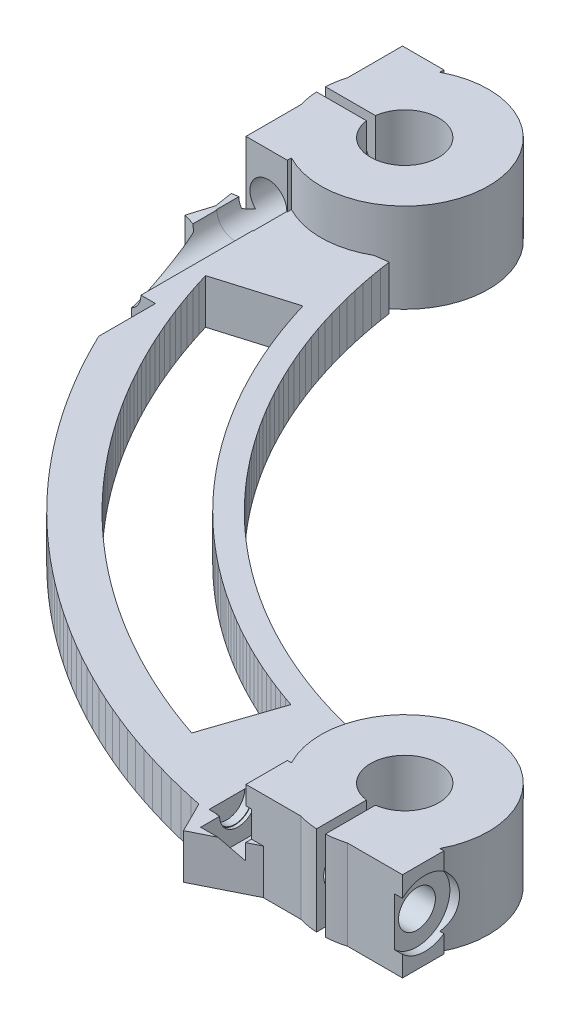
SolidWorks part; units mm, degrees
other "Suspension Travel Stop Plate"
ref_plane "Front Plane" through (0, 0, 0) normal (0, 0, 1) x (1, 0, 0)
ref_plane "Top Plane" through (0, 0, 0) normal (0, 1, 0) x (1, 0, 0)
ref_plane "Right Plane" through (0, 0, 0) normal (1, 0, 0) x (0, 0, -1)
sketch3d "Main Profile Sketch datum points"
  point P0 (0, -120, 0)
  point P1 (10, -120, 0)
  point P2 (0, -120, 10)
ref_plane "Main Profile Sketch plane" through (0, -120, 0) normal (0, -1, 0) x (-1, 0, 0)
sketch "Main Profile Sketch" plane through (0, -120, 0) normal (0, -1, 0) x (-1, 0, 0)
  line L0 (49.2917, -53.5) -> (49.2917, -57.2)
  line L1 (49.2917, -57.2) -> (54.1917, -57.2)
  line L2 (55.8917, -53.0237) -> (55.8917, -57.4893)
  line L3 (56.6917, -53.0237) -> (56.6917, -57.4893)
  line L4 (58.3917, -57.2) -> (61.7474, -57.2)
  line L5 (61.7474, -57.2) -> (66.5028, -59.5777)
  line L6 (66.5028, -59.5777) -> (67.8774, -56.8285)
  line L7 (68.7463, -56.647) -> (67.8774, -56.8285)
  line L8 (69.9299, -56.3737) -> (68.7463, -56.647)
  line L9 (71.1075, -56.0758) -> (69.9299, -56.3737)
  line L10 (72.2786, -55.7532) -> (71.1075, -56.0758)
  line L11 (73.4427, -55.4061) -> (72.2786, -55.7532)
  line L12 (74.5993, -55.0348) -> (73.4427, -55.4061)
  line L13 (75.7478, -54.6393) -> (74.5993, -55.0348)
  line L14 (76.8879, -54.2199) -> (75.7478, -54.6393)
  line L15 (78.0188, -53.7767) -> (76.8879, -54.2199)
  line L16 (79.1403, -53.3098) -> (78.0188, -53.7767)
  line L17 (80.2517, -52.8197) -> (79.1403, -53.3098)
  line L18 (81.3526, -52.3063) -> (80.2517, -52.8197)
  line L19 (82.4425, -51.77) -> (81.3526, -52.3063)
  line L20 (83.521, -51.211) -> (82.4425, -51.77)
  line L21 (84.5875, -50.6295) -> (83.521, -51.211)
  line L22 (85.6416, -50.0258) -> (84.5875, -50.6295)
  line L23 (86.6828, -49.4002) -> (85.6416, -50.0258)
  line L24 (87.7107, -48.7529) -> (86.6828, -49.4002)
  line L25 (88.7248, -48.0842) -> (87.7107, -48.7529)
  line L26 (89.7247, -47.3944) -> (88.7248, -48.0842)
  line L27 (90.7099, -46.6838) -> (89.7247, -47.3944)
  line L28 (91.6801, -45.9528) -> (90.7099, -46.6838)
  line L29 (92.6347, -45.2016) -> (91.6801, -45.9528)
  line L30 (93.5733, -44.4306) -> (92.6347, -45.2016)
  line L31 (94.4956, -43.6401) -> (93.5733, -44.4306)
  line L32 (95.4012, -42.8304) -> (94.4956, -43.6401)
  line L33 (96.2896, -42.002) -> (95.4012, -42.8304)
  line L34 (97.1604, -41.1551) -> (96.2896, -42.002)
  line L35 (98.0134, -40.2902) -> (97.1604, -41.1551)
  line L36 (98.848, -39.4076) -> (98.0134, -40.2902)
  line L37 (99.6639, -38.5077) -> (98.848, -39.4076)
  line L38 (100.4609, -37.591) -> (99.6639, -38.5077)
  line L39 (101.2384, -36.6577) -> (100.4609, -37.591)
  line L40 (101.9963, -35.7084) -> (101.2384, -36.6577)
  line L41 (102.7341, -34.7434) -> (101.9963, -35.7084)
  line L42 (103.4515, -33.7631) -> (102.7341, -34.7434)
  line L43 (104.1482, -32.7681) -> (103.4515, -33.7631)
  line L44 (104.824, -31.7587) -> (104.1482, -32.7681)
  line L45 (105.4784, -30.7353) -> (104.824, -31.7587)
  line L46 (106.1113, -29.6985) -> (105.4784, -30.7353)
  line L47 (106.7224, -28.6486) -> (106.1113, -29.6985)
  line L48 (107.3113, -27.5862) -> (106.7224, -28.6486)
  line L49 (107.8778, -26.5117) -> (107.3113, -27.5862)
  line L50 (108.4217, -25.4255) -> (107.8778, -26.5117)
  line L51 (108.9427, -24.3282) -> (108.4217, -25.4255)
  line L52 (109.4407, -23.2202) -> (108.9427, -24.3282)
  line L53 (109.9153, -22.1021) -> (109.4407, -23.2202)
  line L54 (110.3664, -20.9742) -> (109.9153, -22.1021)
  line L55 (110.7938, -19.8372) -> (110.3664, -20.9742)
  line L56 (111.1973, -18.6914) -> (110.7938, -19.8372)
  line L57 (111.5767, -17.5375) -> (111.1973, -18.6914)
  line L58 (111.9319, -16.3758) -> (111.5767, -17.5375)
  line L59 (112.2626, -15.207) -> (111.9319, -16.3758)
  line L60 (112.5688, -14.0315) -> (112.2626, -15.207)
  line L61 (112.8503, -12.8498) -> (112.5688, -14.0315)
  line L62 (112.9979, -12.1673) -> (112.8503, -12.8498)
  line L63 (112.9979, -12.1673) -> (114.1148, -11.8237)
  line L64 (114.1148, -11.8237) -> (113.468, -9.7218)
  line L65 (113.5456, -9.2731) -> (113.468, -9.7218)
  line L66 (113.7272, -8.072) -> (113.5456, -9.2731)
  line L67 (112.9258, -7.9594) -> (113.7272, -8.072)
  line L68 (112.9258, -7.9594) -> (112.6306, -7)
  line L69 (112.6306, -7) -> (113.4917, -7)
  line L70 (113.4917, -2.1) -> (113.4917, -7)
  line L71 (109.2649, -0.4) -> (113.781, -0.4)
  line L72 (103.4243, -0.8823) -> (103.3765, -0.897)
  line L73 (109.2068, 0.897) -> (109.159, 0.8823)
  line L74 (109.2649, 0.4) -> (113.781, 0.4)
  line L75 (113.4917, 7) -> (113.4917, 2.1)
  line L76 (109.7917, 7) -> (113.4917, 7)
  line L77 (109.7917, 7) -> (109.7917, 6.6332)
  line L78 (101.3488, -6.3324) -> (102.5527, -6.5016)
  line L79 (101.2064, -7.2746) -> (101.3488, -6.3324)
  line L80 (101.0442, -8.2136) -> (101.2064, -7.2746)
  line L81 (100.8623, -9.149) -> (101.0442, -8.2136)
  line L82 (100.6609, -10.0805) -> (100.8623, -9.149)
  line L83 (100.4401, -11.0074) -> (100.6609, -10.0805)
  line L84 (100.1999, -11.9296) -> (100.4401, -11.0074)
  line L85 (99.9404, -12.8465) -> (100.1999, -11.9296)
  line L86 (99.6618, -13.7578) -> (99.9404, -12.8465)
  line L87 (99.3642, -14.6631) -> (99.6618, -13.7578)
  line L88 (99.0477, -15.5619) -> (99.3642, -14.6631)
  line L89 (98.7124, -16.4539) -> (99.0477, -15.5619)
  line L90 (98.3585, -17.3387) -> (98.7124, -16.4539)
  line L91 (97.9862, -18.2159) -> (98.3585, -17.3387)
  line L92 (97.5955, -19.0851) -> (97.9862, -18.2159)
  line L93 (97.1868, -19.9459) -> (97.5955, -19.0851)
  line L94 (96.7601, -20.798) -> (97.1868, -19.9459)
  line L95 (96.3157, -21.6409) -> (96.7601, -20.798)
  line L96 (95.8537, -22.4744) -> (96.3157, -21.6409)
  line L97 (95.3743, -23.298) -> (95.8537, -22.4744)
  line L98 (94.8778, -24.1113) -> (95.3743, -23.298)
  line L99 (94.3644, -24.9141) -> (94.8778, -24.1113)
  line L100 (93.8343, -25.706) -> (94.3644, -24.9141)
  line L101 (93.2877, -26.4866) -> (93.8343, -25.706)
  line L102 (92.7249, -27.2556) -> (93.2877, -26.4866)
  line L103 (92.1461, -28.0126) -> (92.7249, -27.2556)
  line L104 (91.5516, -28.7573) -> (92.1461, -28.0126)
  line L105 (90.9416, -29.4895) -> (91.5516, -28.7573)
  line L106 (90.3165, -30.2086) -> (90.9416, -29.4895)
  line L107 (89.6764, -30.9146) -> (90.3165, -30.2086)
  line L108 (89.0216, -31.607) -> (89.6764, -30.9146)
  line L109 (88.3525, -32.2855) -> (89.0216, -31.607)
  line L110 (87.6693, -32.9498) -> (88.3525, -32.2855)
  line L111 (86.9724, -33.5997) -> (87.6693, -32.9498)
  line L112 (86.262, -34.2349) -> (86.9724, -33.5997)
  line L113 (85.5385, -34.855) -> (86.262, -34.2349)
  line L114 (84.8021, -35.4599) -> (85.5385, -34.855)
  line L115 (84.0533, -36.0492) -> (84.8021, -35.4599)
  line L116 (83.2922, -36.6227) -> (84.0533, -36.0492)
  line L117 (82.5193, -37.1801) -> (83.2922, -36.6227)
  line L118 (81.7349, -37.7212) -> (82.5193, -37.1801)
  line L119 (80.9394, -38.2458) -> (81.7349, -37.7212)
  line L120 (80.133, -38.7536) -> (80.9394, -38.2458)
  line L121 (79.3162, -39.2444) -> (80.133, -38.7536)
  line L122 (78.4893, -39.718) -> (79.3162, -39.2444)
  line L123 (77.6526, -40.1741) -> (78.4893, -39.718)
  line L124 (76.8066, -40.6127) -> (77.6526, -40.1741)
  line L125 (75.9516, -41.0334) -> (76.8066, -40.6127)
  line L126 (75.0879, -41.4361) -> (75.9516, -41.0334)
  line L127 (74.216, -41.8207) -> (75.0879, -41.4361)
  line L128 (73.3363, -42.1869) -> (74.216, -41.8207)
  line L129 (72.449, -42.5346) -> (73.3363, -42.1869)
  line L130 (71.5547, -42.8636) -> (72.449, -42.5346)
  line L131 (70.6537, -43.1739) -> (71.5547, -42.8636)
  line L132 (69.7464, -43.4652) -> (70.6537, -43.1739)
  line L133 (68.8332, -43.7374) -> (69.7464, -43.4652)
  line L134 (67.9144, -43.9905) -> (68.8332, -43.7374)
  line L135 (66.9906, -44.2242) -> (67.9144, -43.9905)
  line L136 (66.0621, -44.4386) -> (66.9906, -44.2242)
  line L137 (65.1293, -44.6335) -> (66.0621, -44.4386)
  line L138 (64.1926, -44.8088) -> (65.1293, -44.6335)
  line L139 (65.0956, -49.9299) -> (64.1926, -44.8088)
  line L140 (65.0956, -49.9299) -> (63.755, -49.2595)
  line L141 (49.2917, -53.5) -> (49.6584, -53.5)
  line L142 (100.8479, -16.4618) -> (101.1044, -15.7502)
  line L143 (101.1044, -15.7502) -> (101.3495, -15.0346)
  line L144 (101.3495, -15.0346) -> (101.5832, -14.3152)
  line L145 (101.5832, -14.3152) -> (101.8054, -13.5922)
  line L146 (101.8054, -13.5922) -> (108.5127, -15.5953)
  line L147 (108.5127, -15.5953) -> (108.2577, -16.4249)
  line L148 (108.2577, -16.4249) -> (107.9896, -17.2503)
  line L149 (107.9896, -17.2503) -> (107.7084, -18.0713)
  line L150 (107.7084, -18.0713) -> (107.4141, -18.8878)
  line L151 (107.4141, -18.8878) -> (107.1068, -19.6995)
  line L152 (107.1068, -19.6995) -> (106.7867, -20.5061)
  line L153 (106.7867, -20.5061) -> (106.4537, -21.3076)
  line L154 (106.4537, -21.3076) -> (106.1081, -22.1037)
  line L155 (106.1081, -22.1037) -> (105.7498, -22.8942)
  line L156 (105.7498, -22.8942) -> (105.379, -23.6788)
  line L157 (105.379, -23.6788) -> (104.9957, -24.4575)
  line L158 (104.9957, -24.4575) -> (104.6, -25.2299)
  line L159 (104.6, -25.2299) -> (104.1922, -25.996)
  line L160 (104.1922, -25.996) -> (103.7721, -26.7555)
  line L161 (103.7721, -26.7555) -> (103.3401, -27.5081)
  line L162 (103.3401, -27.5081) -> (102.8961, -28.2538)
  line L163 (102.8961, -28.2538) -> (102.4402, -28.9924)
  line L164 (102.4402, -28.9924) -> (101.9727, -29.7236)
  line L165 (101.9727, -29.7236) -> (101.4936, -30.4472)
  line L166 (101.4936, -30.4472) -> (101.003, -31.1631)
  line L167 (101.003, -31.1631) -> (100.5011, -31.8712)
  line L168 (100.5011, -31.8712) -> (99.988, -32.5711)
  line L169 (99.988, -32.5711) -> (99.4638, -33.2628)
  line L170 (99.4638, -33.2628) -> (98.9287, -33.9461)
  line L171 (98.9287, -33.9461) -> (98.3827, -34.6207)
  line L172 (98.3827, -34.6207) -> (97.8261, -35.2866)
  line L173 (97.8261, -35.2866) -> (97.2589, -35.9435)
  line L174 (97.2589, -35.9435) -> (96.6814, -36.5913)
  line L175 (96.6814, -36.5913) -> (96.0936, -37.2298)
  line L176 (96.0936, -37.2298) -> (95.4957, -37.8589)
  line L177 (95.4957, -37.8589) -> (94.8878, -38.4784)
  line L178 (94.8878, -38.4784) -> (94.2702, -39.0881)
  line L179 (94.2702, -39.0881) -> (93.643, -39.6879)
  line L180 (93.643, -39.6879) -> (93.0063, -40.2776)
  line L181 (93.0063, -40.2776) -> (92.3602, -40.8572)
  line L182 (92.3602, -40.8572) -> (91.705, -41.4263)
  line L183 (91.705, -41.4263) -> (91.0409, -41.985)
  line L184 (91.0409, -41.985) -> (90.3679, -42.533)
  line L185 (90.3679, -42.533) -> (89.6863, -43.0703)
  line L186 (89.6863, -43.0703) -> (88.9962, -43.5966)
  line L187 (88.9962, -43.5966) -> (88.2978, -44.1118)
  line L188 (88.2978, -44.1118) -> (87.5914, -44.6159)
  line L189 (87.5914, -44.6159) -> (86.8769, -45.1087)
  line L190 (86.8769, -45.1087) -> (86.1547, -45.59)
  line L191 (86.1547, -45.59) -> (85.425, -46.0597)
  line L192 (85.425, -46.0597) -> (84.6879, -46.5178)
  line L193 (84.6879, -46.5178) -> (83.9435, -46.9641)
  line L194 (83.9435, -46.9641) -> (83.1922, -47.3985)
  line L195 (83.1922, -47.3985) -> (82.434, -47.8208)
  line L196 (82.434, -47.8208) -> (81.6692, -48.231)
  line L197 (81.6692, -48.231) -> (80.8979, -48.629)
  line L198 (80.8979, -48.629) -> (80.1204, -49.0147)
  line L199 (80.1204, -49.0147) -> (79.3369, -49.3879)
  line L200 (79.3369, -49.3879) -> (78.5475, -49.7486)
  line L201 (78.5475, -49.7486) -> (77.7525, -50.0967)
  line L202 (77.7525, -50.0967) -> (76.9521, -50.4321)
  line L203 (76.9521, -50.4321) -> (76.1464, -50.7547)
  line L204 (76.1464, -50.7547) -> (75.3357, -51.0644)
  line L205 (75.3357, -51.0644) -> (74.5201, -51.3612)
  line L206 (74.5201, -51.3612) -> (73.6999, -51.645)
  line L207 (73.6999, -51.645) -> (71.464, -45.0117)
  line L208 (71.464, -45.0117) -> (72.1788, -44.7644)
  line L209 (72.1788, -44.7644) -> (72.8896, -44.5057)
  line L210 (72.8896, -44.5057) -> (73.5962, -44.2357)
  line L211 (73.5962, -44.2357) -> (74.2984, -43.9546)
  line L212 (74.2984, -43.9546) -> (74.9961, -43.6623)
  line L213 (74.9961, -43.6623) -> (75.689, -43.3589)
  line L214 (75.689, -43.3589) -> (76.377, -43.0445)
  line L215 (76.377, -43.0445) -> (77.0599, -42.7192)
  line L216 (77.0599, -42.7192) -> (77.7375, -42.3831)
  line L217 (77.7375, -42.3831) -> (78.4097, -42.0362)
  line L218 (78.4097, -42.0362) -> (79.0762, -41.6787)
  line L219 (79.0762, -41.6787) -> (79.737, -41.3106)
  line L220 (79.737, -41.3106) -> (80.3919, -40.932)
  line L221 (80.3919, -40.932) -> (81.0406, -40.543)
  line L222 (81.0406, -40.543) -> (81.6831, -40.1438)
  line L223 (81.6831, -40.1438) -> (82.3191, -39.7344)
  line L224 (82.3191, -39.7344) -> (82.9485, -39.3149)
  line L225 (82.9485, -39.3149) -> (83.5712, -38.8854)
  line L226 (83.5712, -38.8854) -> (84.187, -38.4461)
  line L227 (84.187, -38.4461) -> (84.7956, -37.997)
  line L228 (84.7956, -37.997) -> (85.3971, -37.5383)
  line L229 (85.3971, -37.5383) -> (85.9911, -37.0701)
  line L230 (85.9911, -37.0701) -> (86.5777, -36.5924)
  line L231 (86.5777, -36.5924) -> (87.1565, -36.1055)
  line L232 (87.1565, -36.1055) -> (87.7276, -35.6095)
  line L233 (87.7276, -35.6095) -> (88.2906, -35.1044)
  line L234 (88.2906, -35.1044) -> (88.8456, -34.5904)
  line L235 (88.8456, -34.5904) -> (89.3922, -34.0676)
  line L236 (89.3922, -34.0676) -> (89.9305, -33.5362)
  line L237 (89.9305, -33.5362) -> (90.4603, -32.9963)
  line L238 (90.4603, -32.9963) -> (90.9814, -32.448)
  line L239 (90.9814, -32.448) -> (91.4937, -31.8915)
  line L240 (91.4937, -31.8915) -> (91.9971, -31.3269)
  line L241 (91.9971, -31.3269) -> (92.4914, -30.7543)
  line L242 (92.4914, -30.7543) -> (92.9765, -30.174)
  line L243 (92.9765, -30.174) -> (93.4524, -29.586)
  line L244 (93.4524, -29.586) -> (93.9188, -28.9905)
  line L245 (93.9188, -28.9905) -> (94.3756, -28.3877)
  line L246 (94.3756, -28.3877) -> (94.8228, -27.7776)
  line L247 (94.8228, -27.7776) -> (95.2603, -27.1605)
  line L248 (95.2603, -27.1605) -> (95.6879, -26.5366)
  line L249 (95.6879, -26.5366) -> (96.1054, -25.9059)
  line L250 (96.1054, -25.9059) -> (96.5129, -25.2686)
  line L251 (96.5129, -25.2686) -> (96.9102, -24.6249)
  line L252 (96.9102, -24.6249) -> (97.2971, -23.975)
  line L253 (97.2971, -23.975) -> (97.6737, -23.319)
  line L254 (97.6737, -23.319) -> (98.0398, -22.6571)
  line L255 (98.0398, -22.6571) -> (98.3953, -21.9894)
  line L256 (98.3953, -21.9894) -> (98.7401, -21.3161)
  line L257 (98.7401, -21.3161) -> (99.0742, -20.6375)
  line L258 (99.0742, -20.6375) -> (99.3974, -19.9536)
  line L259 (99.3974, -19.9536) -> (99.7096, -19.2647)
  line L260 (99.7096, -19.2647) -> (100.0109, -18.5709)
  line L261 (100.0109, -18.5709) -> (100.3011, -17.8723)
  line L262 (100.3011, -17.8723) -> (100.5801, -17.1693)
  line L263 (100.5801, -17.1693) -> (100.8479, -16.4618)
  arc A0 (54.1917, -57.2) -> (55.8917, -57.4893) centre (56.2917, -50) ccw
  arc A1 (56.2917, -46.95) -> (55.8917, -53.0237) centre (56.2917, -50) ccw
  arc A2 (56.6917, -53.0237) -> (56.2917, -46.95) centre (56.2917, -50) ccw
  arc A3 (56.6917, -57.4893) -> (58.3917, -57.2) centre (56.2917, -50) ccw
  arc A4 (113.4917, -2.1) -> (113.781, -0.4) centre (106.2917, 0) ccw
  arc A5 (103.4243, -0.8823) -> (109.2649, -0.4) centre (106.2917, 0) ccw
  arc A6 (109.2068, 0.897) -> (103.3765, -0.897) centre (106.2917, 0) ccw
  arc A7 (109.2649, 0.4) -> (109.159, 0.8823) centre (106.2917, 0) ccw
  arc A8 (113.781, 0.4) -> (113.4917, 2.1) centre (106.2917, 0) ccw
  arc A9 (109.7917, 6.6332) -> (102.5527, -6.5016) centre (106.2917, 0) ccw
  arc A10 (63.755, -49.2595) -> (49.6584, -53.5) centre (56.2917, -50) ccw
extrude "Main Extrusion" add sketch "Main Profile Sketch" against normal blind 4 separate body
sketch3d "Detail Profile 2 Sketch datum points"
  point P0 (0, -116, 0)
  point P1 (10, -116, 0)
  point P2 (0, -116, 10)
ref_plane "Detail Profile 2 Sketch plane" through (0, -116, 0) normal (0, -1, 0) x (-1, 0, 0)
sketch "Detail Profile 2 Sketch" plane through (0, -116, 0) normal (0, -1, 0) x (-1, 0, 0)
  line L0 (49.2917, -53.5) -> (49.2917, -57.2)
  line L1 (49.2917, -57.2) -> (54.1917, -57.2)
  line L2 (55.8917, -53.0237) -> (55.8917, -57.4893)
  line L3 (56.6917, -53.0237) -> (56.6917, -57.4893)
  line L4 (58.3917, -57.2) -> (63.2917, -57.2)
  line L5 (63.2917, -53.5) -> (63.2917, -57.2)
  line L6 (62.9249, -53.5) -> (63.2917, -53.5)
  line L7 (49.2917, -53.5) -> (49.6584, -53.5)
  line L8 (109.7917, -7) -> (113.4917, -7)
  line L9 (113.4917, -2.1) -> (113.4917, -7)
  line L10 (109.3153, -0.4) -> (113.781, -0.4)
  line L11 (109.3153, 0.4) -> (113.781, 0.4)
  line L12 (113.4917, 7) -> (113.4917, 2.1)
  line L13 (109.7917, 7) -> (113.4917, 7)
  line L14 (109.7917, 7) -> (109.7917, 6.6332)
  line L15 (109.7917, -6.6332) -> (109.7917, -7)
  arc A0 (54.1917, -57.2) -> (55.8917, -57.4893) centre (56.2917, -50) ccw
  arc A1 (56.2917, -46.95) -> (55.8917, -53.0237) centre (56.2917, -50) ccw
  arc A2 (56.6917, -53.0237) -> (56.2917, -46.95) centre (56.2917, -50) ccw
  arc A3 (56.6917, -57.4893) -> (58.3917, -57.2) centre (56.2917, -50) ccw
  arc A4 (62.9249, -53.5) -> (49.6584, -53.5) centre (56.2917, -50) ccw
  arc A5 (113.4917, -2.1) -> (113.781, -0.4) centre (106.2917, 0) ccw
  arc A6 (109.3153, 0.4) -> (109.3153, -0.4) centre (106.2917, 0) ccw
  arc A7 (113.781, 0.4) -> (113.4917, 2.1) centre (106.2917, 0) ccw
  arc A8 (109.7917, 6.6332) -> (109.7917, -6.6332) centre (106.2917, 0) ccw
extrude "Detail Extrusion 2" add sketch "Detail Profile 2 Sketch" against normal blind 4
sketch3d "Stop Clamp Bore 1 profile datum points"
  point P0 (-111.4917, -116, -10)
  point P1 (-101.4917, -116, -10)
  point P2 (-111.4917, -106, -10)
ref_plane "Stop Clamp Bore 1 profile plane" through (0, 0, -10) normal (0, 0, 1) x (1, 0, 0)
sketch "Stop Clamp Bore 1 profile" plane through (0, 0, -10) normal (0, 0, 1) x (1, 0, 0)
  circle A0 centre (-111.4917, -116) radius 1.65
extrude "Stop Clamp Bore 1" cut sketch "Stop Clamp Bore 1 profile" along normal blind 20
sketch3d "Stop Clamp Bore 2 profile datum points"
  point P0 (-66.2917, -116, 55.2)
  point P1 (-66.2917, -106, 55.2)
  point P2 (-66.2917, -116, 65.2)
ref_plane "Stop Clamp Bore 2 profile plane" through (-66.2917, 0, 0) normal (1, 0, 0) x (0, 0, -1)
sketch "Stop Clamp Bore 2 profile" plane through (-66.2917, 0, 0) normal (1, 0, 0) x (0, 0, -1)
  circle A0 centre (-55.2, -116) radius 1.65
extrude "Stop Clamp Bore 2" cut sketch "Stop Clamp Bore 2 profile" along normal blind 20
sketch3d "Stop Clamp Bore 3 profile datum points"
  point P0 (-111.4917, -116, -11)
  point P1 (-101.4917, -116, -11)
  point P2 (-111.4917, -106, -11)
ref_plane "Stop Clamp Bore 3 profile plane" through (0, 0, -11) normal (0, 0, 1) x (1, 0, 0)
sketch "Stop Clamp Bore 3 profile" plane through (0, 0, -11) normal (0, 0, 1) x (1, 0, 0)
  circle A0 centre (-111.4917, -116) radius 1.6
extrude "Stop Clamp Bore 3" cut sketch "Stop Clamp Bore 3 profile" along normal blind 40
sketch3d "Stop Clamp Bore 4 profile datum points"
  point P0 (-111.4917, -116, 20)
  point P1 (-101.4917, -116, 20)
  point P2 (-111.4917, -106, 20)
ref_plane "Stop Clamp Bore 4 profile plane" through (0, 0, 20) normal (0, 0, 1) x (1, 0, 0)
sketch "Stop Clamp Bore 4 profile" plane through (0, 0, 20) normal (0, 0, 1) x (1, 0, 0)
  circle A0 centre (-111.4917, -116) radius 2.9
extrude "Stop Clamp Bore 4" cut sketch "Stop Clamp Bore 4 profile" along normal blind 15
sketch3d "Stop Clamp Bore 5 profile datum points"
  point P0 (-67, -116, 55.2)
  point P1 (-67, -106, 55.2)
  point P2 (-67, -116, 65.2)
ref_plane "Stop Clamp Bore 5 profile plane" through (-67, 0, 0) normal (1, 0, 0) x (0, 0, -1)
sketch "Stop Clamp Bore 5 profile" plane through (-67, 0, 0) normal (1, 0, 0) x (0, 0, -1)
  circle A0 centre (-55.2, -116) radius 1.6
extrude "Stop Clamp Bore 5" cut sketch "Stop Clamp Bore 5 profile" along normal blind 23
sketch3d "Stop Clamp Bore 6 profile datum points"
  point P0 (-50, -116, 55.2)
  point P1 (-50, -106, 55.2)
  point P2 (-50, -116, 65.2)
ref_plane "Stop Clamp Bore 6 profile plane" through (-50, 0, 0) normal (1, 0, 0) x (0, 0, -1)
sketch "Stop Clamp Bore 6 profile" plane through (-50, 0, 0) normal (1, 0, 0) x (0, 0, -1)
  circle A0 centre (-55.2, -116) radius 2.95
extrude "Stop Clamp Bore 6" cut sketch "Stop Clamp Bore 6 profile" along normal blind 6
sketch3d "Captured Nut Sketch datum points"
  point P0 (-66, -116, 55.2)
  point P1 (-66, -106, 55.2)
  point P2 (-66, -116, 65.2)
ref_plane "Captured Nut Sketch plane" through (-66, 0, 0) normal (1, 0, 0) x (0, 0, -1)
sketch "Captured Nut Sketch" plane through (-66, 0, 0) normal (1, 0, 0) x (0, 0, -1)
  line L0 (-56.8743, -113.1) -> (-58.5486, -116)
  line L1 (-58.5486, -116) -> (-56.8743, -118.9)
  line L2 (-56.8743, -118.9) -> (-53.5257, -118.9)
  line L3 (-53.5257, -118.9) -> (-51.8514, -116)
  line L4 (-51.8514, -116) -> (-53.5257, -113.1)
  line L5 (-53.5257, -113.1) -> (-56.8743, -113.1)
extrude "Captured Nut Pocket" cut sketch "Captured Nut Sketch" along normal blind 3.2
